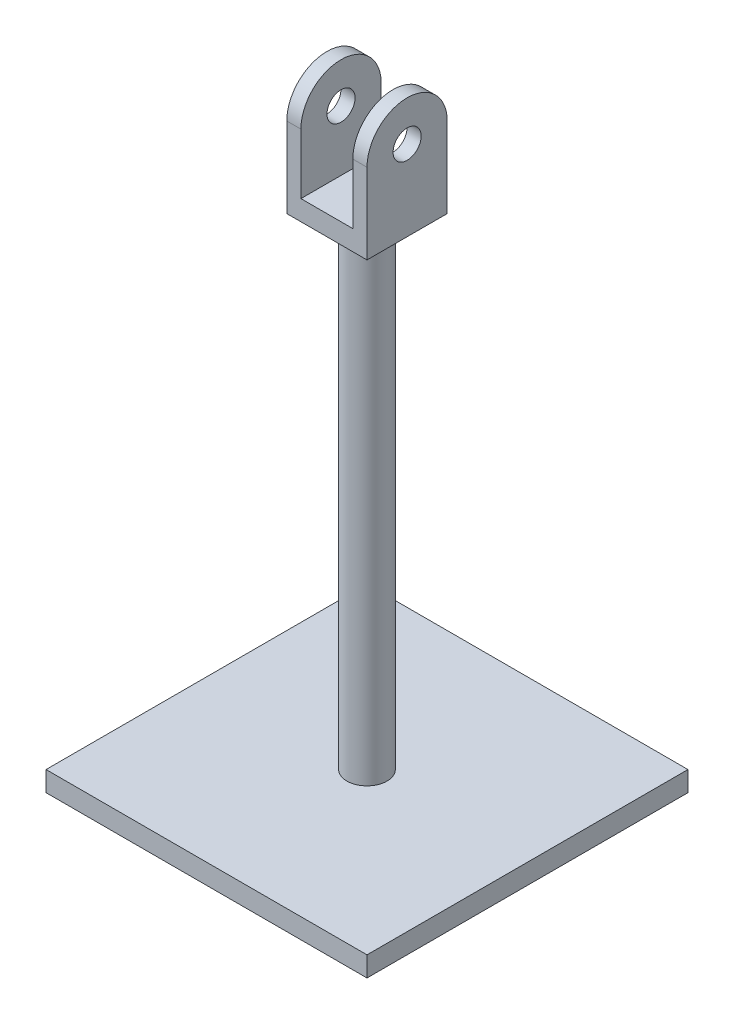
SolidWorks part; units mm, degrees
ref_plane "Plano frontal" through (0, 0, 0) normal (0, 0, 1) x (1, 0, 0)
ref_plane "Plano superior" through (0, 0, 0) normal (0, 1, 0) x (1, 0, 0)
ref_plane "Plano direito" through (0, 0, 0) normal (1, 0, 0) x (0, 0, -1)
sketch "Esboço10" plane through (0, 0, 0) normal (0, 1, 0) x (1, 0, 0)
  line L1 (-40, 40) -> (40, 40)
  line L2 (-40, 40) -> (-40, -40)
  line L3 (-40, -40) -> (40, -40)
  line L4 (40, 40) -> (40, -40)
  line L5 (-40, 40) -> (40, -40) construction
  line L6 (-40, -40) -> (40, 40) construction
  point P0 (0, 0)
  dimension "D1" = 80
  dimension "D2" = 40
extrude "Ressalto-extrusão4" add sketch "Esboço10" along normal blind 5
sketch "Esboço11" plane through (0, 5, 0) normal (0, 1, 0) x (1, 0, 0)
  circle A0 centre (0, 0) radius 5
  dimension "D1" = 10
extrude "Ressalto-extrusão5" add sketch "Esboço11" along normal blind 120
sketch "Esboço12" plane through (0, 125, 0) normal (0, 1, 0) x (1, 0, 0)
  line L1 (-10, 10) -> (10, 10)
  line L2 (-10, 10) -> (-10, -10)
  line L3 (-10, -10) -> (10, -10)
  line L4 (10, 10) -> (10, -10)
  line L5 (-10, 10) -> (10, -10) construction
  line L6 (-10, -10) -> (10, 10) construction
  point P0 (0, 0)
  dimension "D1" = 20
  dimension "D2" = 10
extrude "Ressalto-extrusão6" add sketch "Esboço12" along normal blind 5
sketch "Esboço13" plane through (0, 0, 0) normal (1, 0, 0) x (0, 0, -1)
  line L3 (10, 130) -> (-10, 130)
  line L5 (-10, 145) -> (-10, 130)
  line L6 (10, 145) -> (10, 130)
  arc A0 (10, 145) -> (-10, 145) centre (0, 145) ccw
  circle A1 centre (0, 145) radius 3.5
  dimension "D2" = 20
  dimension "D1" = 7
  dimension "D4" = 145
  dimension "D3" = 20
extrude "Ressalto-extrusão7" add sketch "Esboço13" along normal mid plane 20
sketch "Esboço16" plane through (0, 0, 0) normal (0, 0, 1) x (1, 0, 0)
  line L0 (0, 0) -> (0, 155) construction
  line L1 (10, 155) -> (-10, 155) construction
  line L2 (-10, 135) -> (0, 135) construction
  line L3 (-10, 145) -> (-10, 125) construction
  line L4 (-10, 135) -> (-10, 125) construction
  line L5 (-10, 130) -> (0, 130) construction
  line L7 (-6.4725, 180) -> (6.4725, 180)
  line L8 (-6.4725, 180) -> (-6.4725, 130)
  line L9 (-6.4725, 130) -> (6.4725, 130)
  line L10 (6.4725, 180) -> (6.4725, 130)
  line L11 (-6.4725, 180) -> (6.4725, 130) construction
  line L12 (-6.4725, 130) -> (6.4725, 180) construction
extrude "Corte-extrusão8" cut sketch "Esboço16" against normal mid plane 40
